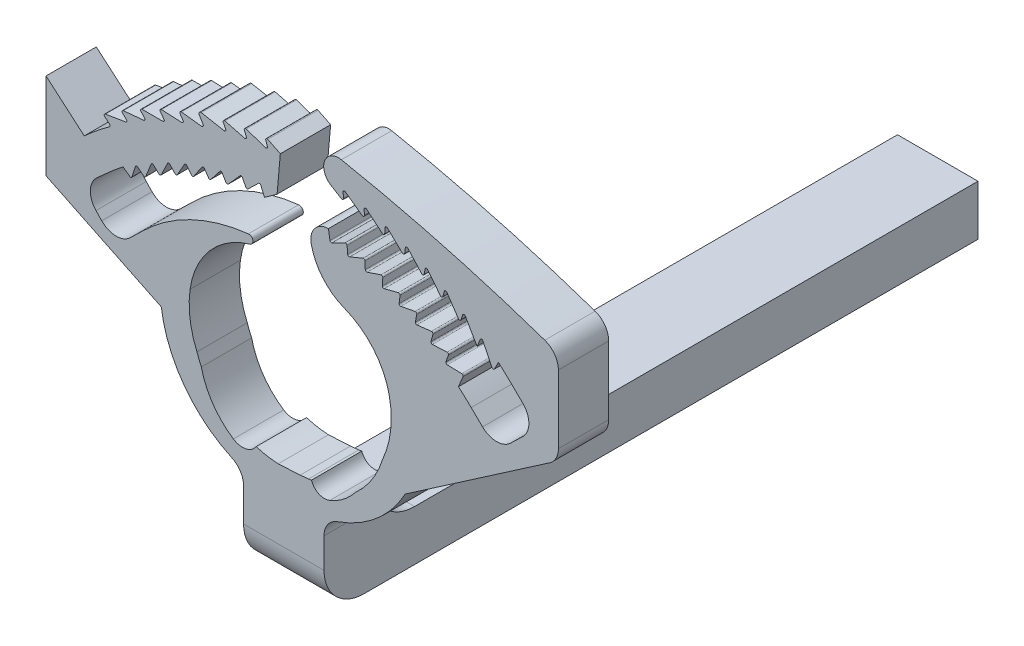
SolidWorks part; units mm, degrees
ref_plane "Front Plane" through (0, 0, 0) normal (0, 0, 1) x (1, 0, 0)
ref_plane "Top Plane" through (0, 0, 0) normal (0, 1, 0) x (1, 0, 0)
ref_plane "Right Plane" through (0, 0, 0) normal (1, 0, 0) x (0, 0, -1)
ref_plane "Plane1" through (0, 0, 0) normal (0, 0, -1) x (-1, 0, 0)
sketch "Sketch1" plane through (0, 0, 0) normal (0, 0, -1) x (-1, 0, 0)
  line L0 (-19.4111, 9.9782) -> (-19.4111, -6.4397)
  line L1 (-19.4111, -6.4397) -> (16.8093, -11.1196)
  line L2 (16.8093, -11.1196) -> (16.8093, 8.8608)
  line L3 (16.8093, 8.8608) -> (14.1048, 6.5428)
  line L4 (12.3103, 8.1586) -> (12.6591, 8.4447)
  line L5 (12.6111, 8.6235) -> (11.1843, 8.8579)
  line L6 (11.131, 9.032) -> (11.4058, 9.2915)
  line L7 (11.3455, 9.4666) -> (9.9055, 9.6014)
  line L8 (9.8403, 9.7714) -> (10.0914, 10.0442)
  line L9 (10.0166, 10.2146) -> (8.5483, 10.2146)
  line L10 (8.469, 10.3796) -> (8.737, 10.7149)
  line L11 (8.653, 10.8799) -> (7.2075, 10.8139)
  line L12 (7.1193, 10.9731) -> (7.3343, 11.2844)
  line L13 (7.239, 11.4431) -> (5.8014, 11.2768)
  line L14 (5.7023, 11.4295) -> (5.9764, 11.8925)
  line L15 (5.8278, 12.1049) -> (4.2192, 11.8044)
  line L16 (4.1097, 11.9499) -> (4.2794, 12.2882)
  line L17 (4.163, 12.4321) -> (2.7617, 12.068)
  line L18 (2.6424, 12.2054) -> (2.7881, 12.5548)
  line L19 (2.6619, 12.6902) -> (1.2903, 12.2295)
  line L20 (1.1617, 12.3583) -> (1.2758, 12.6967)
  line L21 (1.1344, 12.8202) -> (0.2455, 12.3796)
  line L22 (0.2455, 12.3796) -> (0.475, 9.7887)
  line L23 (0.475, 9.7887) -> (1.367, 9.1466)
  line L24 (1.367, 9.1466) -> (1.6241, 9.7632)
  line L25 (1.7885, 9.7972) -> (2.525, 9.0845)
  line L26 (2.6865, 9.1119) -> (2.924, 9.5854)
  line L27 (3.0903, 9.6078) -> (3.9219, 8.6823)
  line L28 (4.0849, 8.6984) -> (4.3549, 9.1543)
  line L29 (4.5224, 9.165) -> (5.152, 8.3573)
  line L30 (5.3158, 8.3621) -> (5.6169, 8.798)
  line L31 (5.7848, 8.797) -> (6.3563, 7.9478)
  line L32 (6.5199, 7.9411) -> (6.8508, 8.355)
  line L33 (7.0182, 8.3423) -> (7.5288, 7.4557)
  line L34 (7.6916, 7.4376) -> (8.0506, 7.8275)
  line L35 (8.2167, 7.8031) -> (8.664, 6.8835)
  line L36 (8.8252, 6.8541) -> (9.2105, 7.218)
  line L37 (9.3745, 7.1821) -> (9.7564, 6.2341)
  line L38 (9.9151, 6.1935) -> (10.3249, 6.5297)
  line L39 (10.486, 6.4825) -> (10.7343, 5.7156)
  line L40 (10.8748, 5.669) -> (11.3632, 6.0157)
  line L42 (0.3969, -6.6776) -> (-1.1557, -6.5938)
  line L43 (-1.1557, -6.5938) -> (-1.7508, -6.529)
  line L44 (-3.1556, 9.4978) -> (-3.2637, 8.8278)
  line L45 (-3.4095, 8.7532) -> (-4.3263, 9.2121)
  line L46 (-4.473, 9.1304) -> (-4.5207, 8.6029)
  line L47 (-4.6609, 8.5183) -> (-5.6074, 8.9121)
  line L48 (-5.748, 8.8204) -> (-5.7588, 8.2908)
  line L49 (-5.8928, 8.1966) -> (-6.8645, 8.5235)
  line L50 (-6.9984, 8.4222) -> (-6.9722, 7.8932)
  line L51 (-7.0993, 7.7898) -> (-8.0914, 8.0481)
  line L52 (-8.2179, 7.9377) -> (-8.1549, 7.4119)
  line L53 (-8.2744, 7.2999) -> (-9.2822, 7.4884)
  line L54 (-9.4006, 7.3694) -> (-9.3011, 6.8492)
  line L55 (-9.4125, 6.7292) -> (-10.431, 6.8469)
  line L56 (-10.5409, 6.7199) -> (-10.4053, 6.208)
  line L57 (-10.5081, 6.0804) -> (-11.5323, 6.1268)
  line L58 (-11.633, 5.9925) -> (-11.462, 5.4912)
  line L59 (-11.5557, 5.3569) -> (-12.5806, 5.3317)
  line L60 (-12.6718, 5.1907) -> (-12.3445, 4.4135)
  line L61 (12.3757, 5.1722) -> (14.3057, 3.4479)
  line L62 (-15.169, 7.3172) -> (-14.8968, 6.7791)
  line L63 (-14.715, 6.7803) -> (-14.0741, 8.0876)
  line L64 (-13.8892, 8.0823) -> (-13.6627, 7.5443)
  line L65 (-13.6627, 7.5443) -> (-12.8299, 8.9802)
  line L66 (-12.6458, 8.962) -> (-12.5232, 8.6026)
  line L67 (-12.343, 8.5784) -> (-11.5264, 9.7838)
  line L68 (-11.3441, 9.7528) -> (-11.2468, 9.3857)
  line L69 (-11.0687, 9.349) -> (-10.17, 10.4946)
  line L70 (-9.9903, 10.4509) -> (-9.9189, 10.0779)
  line L71 (-9.7438, 10.0289) -> (-8.7674, 11.1089)
  line L72 (-8.5912, 11.0529) -> (-8.546, 10.6758)
  line L73 (-8.3747, 10.6147) -> (-7.3253, 11.624)
  line L74 (-7.1534, 11.5558) -> (-7.1347, 11.1765)
  line L75 (-6.968, 11.1036) -> (-5.8509, 12.0372)
  line L76 (-5.6841, 11.9572) -> (-5.6919, 11.5775)
  line L77 (-5.5307, 11.4931) -> (-4.3511, 12.3466)
  line L78 (-4.1904, 12.2551) -> (-4.2246, 11.8769)
  line L79 (-4.0697, 11.7815) -> (-3.3153, 12.2508)
  line L80 (-16.1072, 6.4486) -> (-17.9436, 4.6465)
  line L81 (-13.2481, 3.5887) -> (-15.0357, 1.8419)
  line L82 (-15.0357, 1.8419) -> (-17.9436, 4.6465)
  line L83 (10.0976, 2.6706) -> (11.8768, 0.9387)
  line L84 (11.8768, 0.9387) -> (14.3057, 3.4479)
  arc A0 (14.1048, 6.5428) -> (12.3151, 7.9978) centre (-0.148, -9.1601) ccw
  arc A1 (12.3151, 7.9978) -> (12.3103, 8.1586) centre (12.3748, 8.08) cw
  arc A2 (12.6591, 8.4447) -> (12.6111, 8.6235) centre (12.5946, 8.5232) ccw
  arc A3 (11.1843, 8.8579) -> (11.131, 9.032) centre (11.2008, 8.9582) cw
  arc A4 (11.4058, 9.2915) -> (11.3455, 9.4666) centre (11.336, 9.3654) ccw
  arc A5 (9.9055, 9.6014) -> (9.8403, 9.7714) centre (9.915, 9.7026) cw
  arc A6 (10.0914, 10.0442) -> (10.0166, 10.2146) centre (10.0166, 10.113) ccw
  arc A7 (8.5483, 10.2146) -> (8.469, 10.3796) centre (8.5483, 10.3162) cw
  arc A8 (8.737, 10.7149) -> (8.653, 10.8799) centre (8.6576, 10.7784) ccw
  arc A9 (7.2075, 10.8139) -> (7.1193, 10.9731) centre (7.2029, 10.9154) cw
  arc A10 (7.3343, 11.2844) -> (7.239, 11.4431) centre (7.2507, 11.3422) ccw
  arc A11 (5.8014, 11.2768) -> (5.7023, 11.4295) centre (5.7897, 11.3778) cw
  arc A12 (5.9764, 11.8925) -> (5.8278, 12.1049) centre (5.854, 11.965) ccw
  arc A13 (4.2192, 11.8044) -> (4.1097, 11.9499) centre (4.2005, 11.9043) cw
  arc A14 (4.2794, 12.2882) -> (4.163, 12.4321) centre (4.1886, 12.3337) ccw
  arc A15 (2.7617, 12.068) -> (2.6424, 12.2054) centre (2.7362, 12.1663) cw
  arc A16 (2.7881, 12.5548) -> (2.6619, 12.6902) centre (2.6943, 12.5939) ccw
  arc A17 (1.2903, 12.2295) -> (1.1617, 12.3583) centre (1.258, 12.3258) cw
  arc A18 (1.2758, 12.6967) -> (1.1344, 12.8202) centre (1.1795, 12.7292) ccw
  arc A19 (1.6241, 9.7632) -> (1.7885, 9.7972) centre (1.7179, 9.7241) cw
  arc A20 (2.525, 9.0845) -> (2.6865, 9.1119) centre (2.5957, 9.1575) ccw
  arc A21 (2.924, 9.5854) -> (3.0903, 9.6078) centre (3.0148, 9.5399) cw
  arc A22 (3.9219, 8.6823) -> (4.0849, 8.6984) centre (3.9975, 8.7502) ccw
  arc A23 (4.3549, 9.1543) -> (4.5224, 9.165) centre (4.4423, 9.1025) cw
  arc A24 (5.152, 8.3573) -> (5.3158, 8.3621) centre (5.2322, 8.4198) ccw
  arc A25 (5.6169, 8.798) -> (5.7848, 8.797) centre (5.7005, 8.7403) cw
  arc A26 (6.3563, 7.9478) -> (6.5199, 7.9411) centre (6.4406, 8.0045) ccw
  arc A27 (6.8508, 8.355) -> (7.0182, 8.3423) centre (6.9301, 8.2916) cw
  arc A28 (7.5288, 7.4557) -> (7.6916, 7.4376) centre (7.6169, 7.5064) ccw
  arc A29 (8.0506, 7.8275) -> (8.2167, 7.8031) centre (8.1253, 7.7587) cw
  arc A30 (8.664, 6.8835) -> (8.8252, 6.8541) centre (8.7554, 6.9279) ccw
  arc A31 (9.2105, 7.218) -> (9.3745, 7.1821) centre (9.2803, 7.1442) cw
  arc A32 (9.7564, 6.2341) -> (9.9151, 6.1935) centre (9.8506, 6.272) ccw
  arc A33 (10.3249, 6.5297) -> (10.486, 6.4825) centre (10.3894, 6.4512) cw
  arc A34 (10.7343, 5.7156) -> (10.8748, 5.669) centre (10.8216, 5.7439) ccw
  arc A35 (11.3632, 6.0157) -> (12.3757, 5.1722) centre (-0.2794, -8.9916) cw
  arc A36 (10.0976, 2.6706) -> (2.5051, 6.3472) centre (1.0922, -6.2484) ccw
  arc A37 (2.5051, 6.3472) -> (2.3903, 5.7706) centre (2.4722, 6.054) ccw
  arc A38 (2.3903, 5.7706) -> (6.6239, 0.8955) centre (0.7391, 0.061) cw
  arc A39 (6.6239, 0.8955) -> (6.1373, -2.6916) centre (0.0406, -0.0381) cw
  arc A40 (6.1373, -2.6916) -> (5.8298, -3.4617) centre (-1.7203, 0) cw
  arc A41 (5.8298, -3.4617) -> (3.5647, -6.7378) centre (0.6045, -2.2701) cw
  arc A42 (3.5647, -6.7378) -> (1.9558, -6.4054) centre (2.9253, -5.7728) cw
  arc A43 (1.9558, -6.4054) -> (0.3969, -6.6776) centre (0.0406, -0.0381) cw
  arc A44 (-1.7508, -6.529) -> (-1.9558, -6.5006) centre (-0.9398, 0.0762) cw
  arc A45 (-1.9558, -6.5006) -> (-3.2526, -7.0934) centre (-2.8796, -6.1946) cw
  arc A46 (-3.2526, -7.0934) -> (-5.0474, -5.7142) centre (-1.5767, -3.0552) cw
  arc A47 (-5.0474, -5.7142) -> (-6.9923, -2.6904) centre (-0.6309, -0.7361) cw
  arc A48 (-6.9923, -2.6904) -> (-7.4539, 1.4376) centre (-0.9398, 0.0762) cw
  arc A49 (-7.4539, 1.4376) -> (-4.2829, 5.1855) centre (-2.4067, 0.3828) cw
  arc A50 (-4.2829, 5.1855) -> (-1.9357, 7.9749) centre (-5.6693, 8.7343) ccw
  arc A51 (-1.9357, 7.9749) -> (-3.1556, 9.4978) centre (-3.1802, 8.2281) ccw
  arc A52 (-3.2637, 8.8278) -> (-3.4095, 8.7532) centre (-3.3641, 8.844) cw
  arc A53 (-4.3263, 9.2121) -> (-4.473, 9.1304) centre (-4.3718, 9.1212) ccw
  arc A54 (-4.5207, 8.6029) -> (-4.6609, 8.5183) centre (-4.6218, 8.6121) cw
  arc A55 (-5.6074, 8.9121) -> (-5.748, 8.8204) centre (-5.6464, 8.8183) ccw
  arc A56 (-5.7588, 8.2908) -> (-5.8928, 8.1966) centre (-5.8604, 8.2929) cw
  arc A57 (-6.8645, 8.5235) -> (-6.9984, 8.4222) centre (-6.8969, 8.4272) ccw
  arc A58 (-6.9722, 7.8932) -> (-7.0993, 7.7898) centre (-7.0737, 7.8882) cw
  arc A59 (-8.0914, 8.0481) -> (-8.2179, 7.9377) centre (-8.117, 7.9498) ccw
  arc A60 (-8.1549, 7.4119) -> (-8.2744, 7.2999) centre (-8.2557, 7.3998) cw
  arc A61 (-9.2822, 7.4884) -> (-9.4006, 7.3694) centre (-9.3008, 7.3885) ccw
  arc A62 (-9.3011, 6.8492) -> (-9.4125, 6.7292) centre (-9.4009, 6.8301) cw
  arc A63 (-10.431, 6.8469) -> (-10.5409, 6.7199) centre (-10.4427, 6.746) ccw
  arc A64 (-10.4053, 6.208) -> (-10.5081, 6.0804) centre (-10.5035, 6.1819) cw
  arc A65 (-11.5323, 6.1268) -> (-11.633, 5.9925) centre (-11.5369, 6.0253) ccw
  arc A66 (-11.462, 5.4912) -> (-11.5557, 5.3569) centre (-11.5582, 5.4585) cw
  arc A67 (-12.5806, 5.3317) -> (-12.6718, 5.1907) centre (-12.5781, 5.2301) ccw
  arc A68 (-12.3445, 4.4135) -> (-13.2481, 3.5887) centre (-0.6716, -9.2817) ccw
  arc A69 (-16.1072, 6.4486) -> (-15.169, 7.3172) centre (-0.6716, -9.2817) cw
  arc A70 (-14.8968, 6.7791) -> (-14.715, 6.7803) centre (-14.8062, 6.825) ccw
  arc A71 (-14.0741, 8.0876) -> (-13.8892, 8.0823) centre (-13.9829, 8.0429) cw
  arc A72 (-12.8299, 8.9802) -> (-12.6458, 8.962) centre (-12.742, 8.9292) cw
  arc A73 (-12.5232, 8.6026) -> (-12.343, 8.5784) centre (-12.4271, 8.6354) ccw
  arc A74 (-11.5264, 9.7838) -> (-11.3441, 9.7528) centre (-11.4423, 9.7268) cw
  arc A75 (-11.2468, 9.3857) -> (-11.0687, 9.349) centre (-11.1486, 9.4117) ccw
  arc A76 (-10.17, 10.4946) -> (-9.9903, 10.4509) centre (-10.0901, 10.4318) cw
  arc A77 (-9.9189, 10.0779) -> (-9.7438, 10.0289) centre (-9.8191, 10.097) ccw
  arc A78 (-8.7674, 11.1089) -> (-8.5912, 11.0529) centre (-8.692, 11.0408) cw
  arc A79 (-8.546, 10.6758) -> (-8.3747, 10.6147) centre (-8.4451, 10.6879) ccw
  arc A80 (-7.3253, 11.624) -> (-7.1534, 11.5558) centre (-7.2549, 11.5508) cw
  arc A81 (-7.1347, 11.1765) -> (-6.968, 11.1036) centre (-7.0332, 11.1815) ccw
  arc A82 (-5.8509, 12.0372) -> (-5.6841, 11.9572) centre (-5.7857, 11.9593) cw
  arc A83 (-5.6919, 11.5775) -> (-5.5307, 11.4931) centre (-5.5903, 11.5754) ccw
  arc A84 (-4.3511, 12.3466) -> (-4.1904, 12.2551) centre (-4.2916, 12.2642) cw
  arc A85 (-4.2246, 11.8769) -> (-4.0697, 11.7815) centre (-4.1234, 11.8677) ccw
  arc A86 (-3.3153, 12.2508) -> (-4.0703, 14.1698) centre (-3.8691, 13.141) ccw
  arc A87 (-4.0703, 14.1698) -> (-19.4111, 9.9782) centre (16.6947, -91.9972) ccw
  dimension "D1" = 1.802
extrude "Boss-Extrude1" add sketch "Sketch1" against normal blind 3.556
ref_plane "Plane2" through (0, 0, 25.4) normal (0, 0, 1) x (1, 0, 0)
sketch "Sketch3" plane through (0, 0, 25.4) normal (0, 0, 1) x (1, 0, 0)
  line L1 (2.0453, -8.539) -> (2.0453, -9.4335)
  line L2 (2.0453, -9.4335) -> (19.558, -7.4076)
  line L3 (19.558, -7.4076) -> (19.558, -6.2763)
  arc A0 (8.581, -4.0415) -> (2.0453, -8.539) centre (0.9321, 0.0762) cw
  spline S0 degree 1 poles (19.558, 3.5052) (19.558, -6.2763) knots 1.221294 1.221294 3.021354 3.021354
  spline S1 degree 1 poles (8.581, -4.0415) (9.8709, -3.1547) (18.5671, 2.8239) (19.558, 3.5052) knots -0.148329 -0.148329 0 1 1.113948 1.113948
extrude "Cut-Extrude1" cut sketch "Sketch3" against normal through all
sketch "Sketch4" plane through (0, 0, 25.4) normal (0, 0, 1) x (1, 0, 0)
  line L1 (-16.6624, 2.6771) -> (-17.2005, 2.9661)
  line L2 (-17.2005, 2.9661) -> (-17.2005, -12.1566)
  line L3 (-17.2005, -12.1566) -> (1.0623, -9.2684)
  line L4 (1.0623, -9.2684) -> (1.0623, -8.666)
  arc A0 (1.0623, -8.666) -> (-8.6609, -1.2025) centre (-0.0508, -0.0508) cw
  spline S0 degree 1 poles (-16.6624, 2.6771) (-15.8033, 2.2605) (-11.6994, 0.2707) (-8.6609, -1.2025) knots -0.20934 -0.20934 0 1 1.740407 1.740407
extrude "Cut-Extrude2" cut sketch "Sketch4" against normal through all
scale "Scale1" scale about origin uniform scaling yes scale factor 1.785714
fillet "Fillet2" radius 2.54 6 edges at (34.6627, 17.8182, 3.175) (34.6627, 6.079, 3.175) (26.8495, 3.2891, 3.175) (32.0422, 8.2974, 3.175) (-25.5458, 6.157, 3.175) (-21.2085, 1.6763, 3.175)
sketch "Sketch6" plane through (0, 0, 6.35) normal (0, 0, 1) x (1, 0, 0)
  line L0 (0, 0) -> (0, -15.6026) construction
  line L1 (0, -15.6026) -> (0, -13.0626) construction
  line L2 (0, -13.0626) -> (5.08, -13.0626)
  line L3 (5.08, -13.0626) -> (5.08, -25.7626)
  line L4 (0, -13.0626) -> (-5.08, -13.0626)
  line L5 (-5.08, -13.0626) -> (-5.08, -25.7626)
  line L6 (-5.08, -25.7626) -> (5.08, -25.7626)
  arc A0 (-15.4659, -2.1474) -> (1.897, -15.475) centre (-0.0907, -0.0907) ccw construction
  dimension "D1" = 2.54
  dimension "D2" = 5.08
  dimension "D3" = 5.08
  dimension "D4" = 12.7
extrude "Boss-Extrude3" add sketch "Sketch6" against normal blind 82.55
fillet "Fillet1" radius 2.54 3 edges at (0, -13.0626, 0) (-5.08, -14.7786, 3.175) (5.08, -14.9954, 3.175)
sketch "Sketch7" plane through (0, 0, -76.2) normal (0, 0, -1) x (-1, 0, 0)
  line L0 (5.08, -13.0626) -> (5.08, -25.7626) construction
  line L2 (-5.08, -13.0626) -> (-5.08, -19.4126)
  line L3 (-5.08, -19.4126) -> (5.08, -19.4126)
  line L4 (5.08, -13.0626) -> (5.08, -19.4126)
  line L5 (-5.08, -13.0626) -> (-5.08, -10.3592)
  line L6 (-5.08, -10.3592) -> (5.08, -10.3592)
  line L7 (5.08, -10.3592) -> (5.08, -13.0626)
  dimension "D1" = 6.35
extrude "Cut-Extrude3" cut sketch "Sketch7" against normal blind 76.2
fillet "Fillet3" radius 5.08 2 edges at (0, -19.4126, 0) (0, -25.7626, 6.35)
